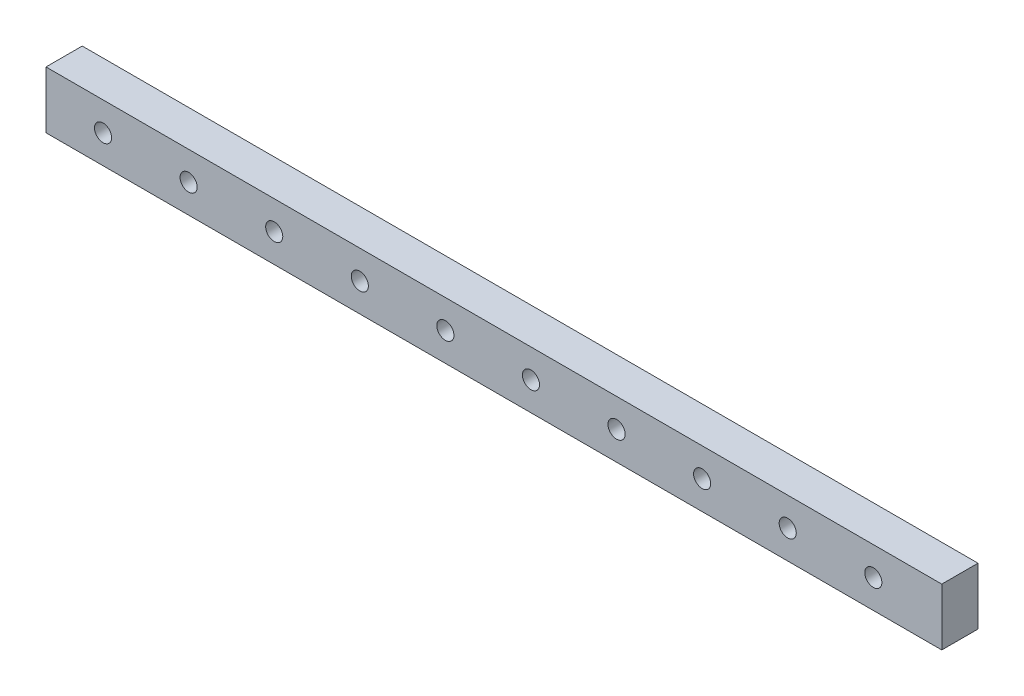
SolidWorks part; units mm, degrees
ref_plane "Front Plane" through (0, 0, 0) normal (0, 0, 1) x (1, 0, 0)
ref_plane "Top Plane" through (0, 0, 0) normal (0, 1, 0) x (1, 0, 0)
ref_plane "Right Plane" through (0, 0, 0) normal (1, 0, 0) x (0, 0, -1)
sketch "Sketch1" plane through (0, 0, 0) normal (0, 0, 1) x (1, 0, 0)
  line L1 (-72.0939, 4.3533) -> (84.9061, 4.3533)
  line L2 (-72.0939, 4.3533) -> (-72.0939, -5.6467)
  line L3 (-72.0939, -5.6467) -> (84.9061, -5.6467)
  line L4 (84.9061, 4.3533) -> (84.9061, -5.6467)
  dimension "D1" = 10
  dimension "D2" = 157
extrude "Boss-Extrude1" add sketch "Sketch1" along normal blind 6.35
sketch "Sketch2" plane through (0, 0, 6.35) normal (0, 0, 1) x (1, 0, 0)
  line L0 (-72.0939, -0.6467) -> (84.9061, -0.6467) construction
  line L1 (-72.0939, 4.3533) -> (-72.0939, -5.6467) construction
  line L2 (84.9061, -5.6467) -> (84.9061, 4.3533) construction
  circle A0 centre (-62.0939, -0.6467) radius 1.5
  circle A1 centre (-47.0939, -0.6467) radius 1.5
  circle A2 centre (-32.0939, -0.6467) radius 1.5
  circle A3 centre (-17.0939, -0.6467) radius 1.5
  circle A4 centre (-2.0939, -0.6467) radius 1.5
  circle A5 centre (12.9061, -0.6467) radius 1.5
  circle A6 centre (27.9061, -0.6467) radius 1.5
  circle A7 centre (42.9061, -0.6467) radius 1.5
  circle A8 centre (57.9061, -0.6467) radius 1.5
  circle A9 centre (72.9061, -0.6467) radius 1.5
  dimension "D2" = 3
  dimension "D3" = 10
  dimension "D1" = 10
extrude "Cut-Extrude1" cut sketch "Sketch2" against normal through all
